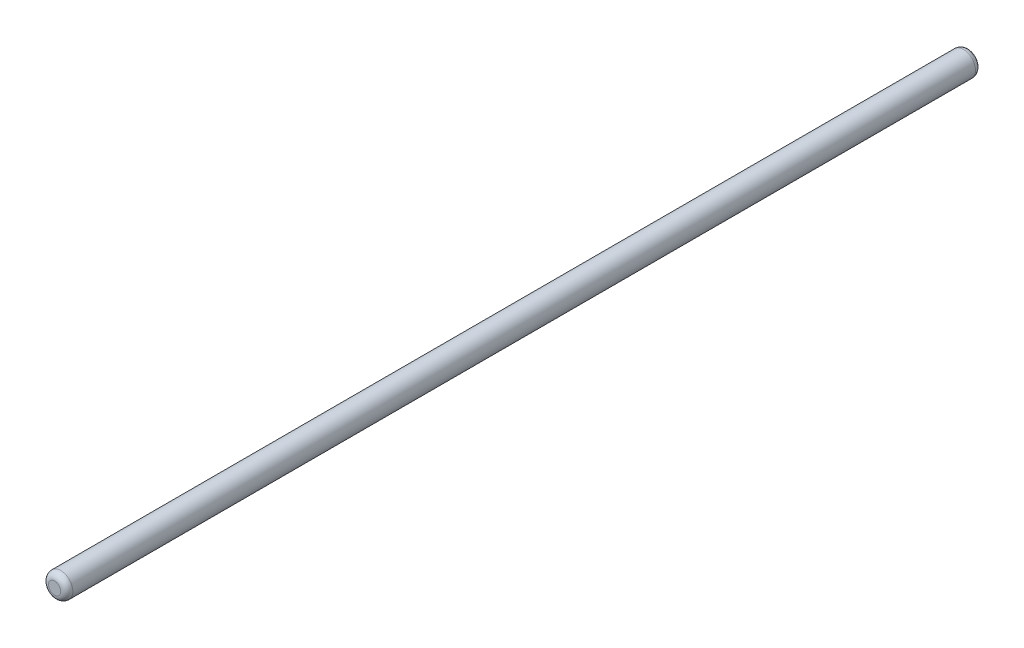
SolidWorks part; units mm, degrees
ref_plane "Front Plane" through (0, 0, 0) normal (0, 0, 1) x (1, 0, 0)
ref_plane "Top Plane" through (0, 0, 0) normal (0, 1, 0) x (1, 0, 0)
ref_plane "Right Plane" through (0, 0, 0) normal (1, 0, 0) x (0, 0, -1)
sketch "Sketch1" plane through (0, 0, 0) normal (0, 0, 1) x (1, 0, 0)
  circle A0 centre (0, 0) radius 4
  dimension "D1" = 8
extrude "Boss-Extrude1" add sketch "Sketch1" along normal blind 300
fillet "Fillet1" radius 2 2 edges at (4, 0, 300) (4, 0, 0)
